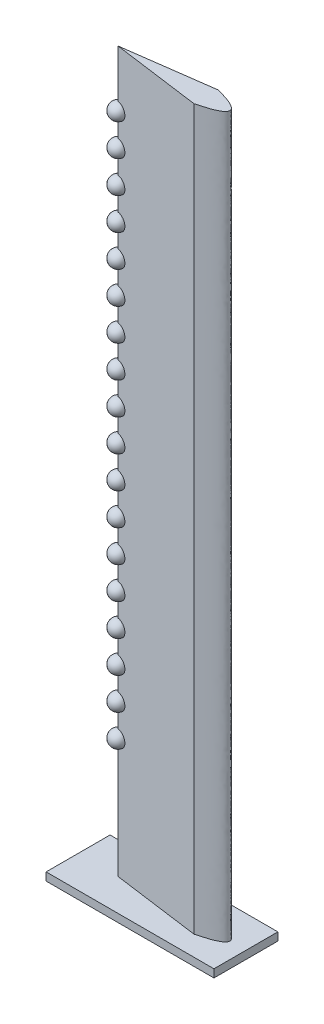
SolidWorks part; units mm, degrees
ref_plane "前视基准面" through (0, 0, 0) normal (0, 0, 1) x (1, 0, 0)
ref_plane "上视基准面" through (0, 0, 0) normal (0, 1, 0) x (1, 0, 0)
ref_plane "右视基准面" through (0, 0, 0) normal (1, 0, 0) x (0, 0, -1)
other "Configuration Table"
sketch "草图1" plane through (0, 0, 0) normal (0, 1, 0) x (1, 0, 0)
  line L0 (0, 0) -> (110, 15)
  line L1 (110, -15) -> (0, 0)
  line L2 (0, 0) -> (140, 0) construction
  spline S0 degree 2 poles (110, 15) (170, 0) (110, -15) knots 0 0 0 1 1 1
  dimension "D2" = 15
  dimension "D1" = 140
  dimension "D3" = 15
  dimension "D4" = 110
  dimension "D5" = 110
extrude "凸台-拉伸1" add sketch "草图1" along normal blind 900
sketch "草图2" plane through (0, 0, 0) normal (0, -1, 0) x (1, 0, 0)
  line L1 (-50, 40) -> (160, 40)
  line L2 (-50, 40) -> (-50, -40)
  line L3 (-50, -40) -> (160, -40)
  line L4 (160, 40) -> (160, -40)
  dimension "D1" = 50
  dimension "D2" = 40
  dimension "D3" = 40
  dimension "D4" = 160
extrude "凸台-拉伸2" add sketch "草图2" along normal blind 10
sketch "草图3" plane through (0, 0, 0) normal (-0.1351, 0, 0.9908) x (0.9908, 0, 0.1351)
  line L0 (0, 900) -> (0, 0) construction
  circle A0 centre (0, 150) radius 10
  dimension "D1" = 20
  dimension "D2" = 150
revolve "旋转2" add sketch "草图3" angle 360 about axis through (0, 900, 0) along (0, -1, 0)
pattern_linear "阵列(线性)1" count 18 spacing 40 along (0, 1, 0) of "旋转2"
ref_plane "基准面1" through (0, 0, 0) normal (0, 0, 1) x (1, 0, 0)
